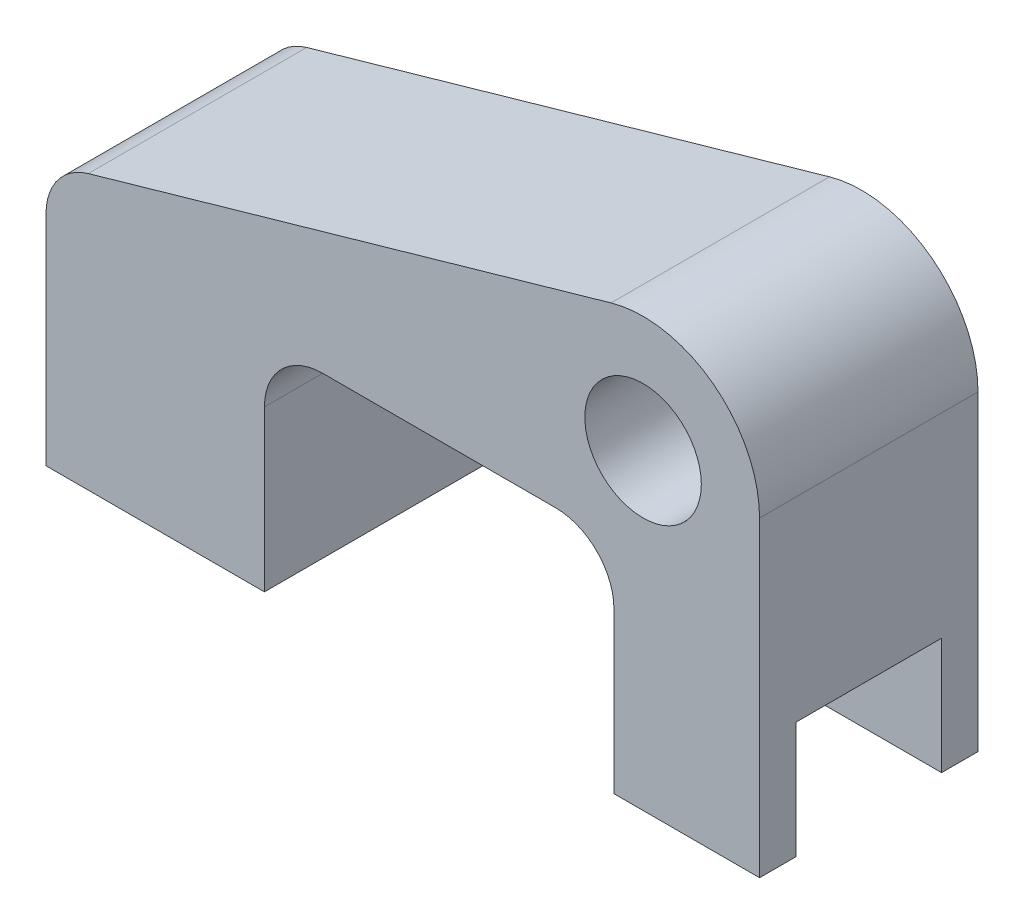
SolidWorks part; units mm, degrees
ref_plane "前视基准面" through (0, 0, 0) normal (0, 0, 1) x (1, 0, 0)
ref_plane "上视基准面" through (0, 0, 0) normal (0, 1, 0) x (1, 0, 0)
ref_plane "右视基准面" through (0, 0, 0) normal (1, 0, 0) x (0, 0, -1)
sketch "草图1" plane through (0, 0, 0) normal (0, 0, 1) x (1, 0, 0)
  line L0 (-20.6748, 2.4852) -> (-5.6748, 2.4852)
  line L1 (-5.6748, 2.4852) -> (-5.6748, 17.4852)
  line L2 (-5.6748, 17.4852) -> (18.3252, 17.4852)
  line L3 (18.3252, 17.4852) -> (18.3252, 2.4852)
  line L4 (18.3252, 2.4852) -> (28.3252, 2.4852)
  line L5 (28.3252, 2.4852) -> (28.3252, 34.4852)
  line L6 (28.3252, 34.4852) -> (-20.6748, 20.4852)
  line L7 (-20.6748, 20.4852) -> (-20.6748, 2.4852)
  dimension "D1" = 18
  dimension "D2" = 32
  dimension "D3" = 24
  dimension "D4" = 15
  dimension "D5" = 10
  dimension "D6" = 15
extrude "凸台-拉伸1" add sketch "草图1" along normal blind 15
fillet "圆角1" radius 8 1 edges at (28.3252, 34.4852, 7.5)
fillet "圆角2" radius 4 1 edges at (-20.6748, 20.4852, 7.5)
sketch "草图2" plane through (0, 0, 15) normal (0, 0, 1) x (1, 0, 0)
  circle A0 centre (20.3252, 23.8794) radius 4
extrude "切除-拉伸1" cut sketch "草图2" against normal through all
fillet "圆角3" radius 4 1 edges at (-5.6748, 17.4852, 7.5)
fillet "圆角4" radius 4 1 edges at (18.3252, 17.4852, 7.5)
sketch "草图3" plane through (0, 2.4852, 0) normal (0, -1, 0) x (1, 0, 0)
  line L0 (-20.6748, 7.5) -> (28.3252, 7.5) construction
  line L1 (-20.6748, 15) -> (-20.6748, 0) construction
  line L2 (28.3252, 15) -> (28.3252, 0) construction
  circle A0 centre (-13.3231, 7.5) radius 1.5
extrude "切除-拉伸2" cut sketch "草图3" against normal blind 10
sketch "草图4" plane through (28.3252, 0, 0) normal (1, 0, 0) x (0, 0, -1)
  line L0 (-7.5, 31.8794) -> (-7.5, 2.4852) construction
  line L1 (0, 31.8794) -> (-15, 31.8794) construction
  line L2 (-15, 2.4852) -> (0, 2.4852) construction
  line L3 (-12.5, 2.4852) -> (-12.5, 10.4852)
  line L4 (-12.5, 10.4852) -> (-2.5, 10.4852)
  line L5 (-2.5, 2.4852) -> (-2.5, 10.4852)
  point P10 (-7.5, 10.4852)
  dimension "D1" = 10
  dimension "D2" = 8
extrude "切除-拉伸3" cut sketch "草图4" against normal blind 20 and the other way through all
